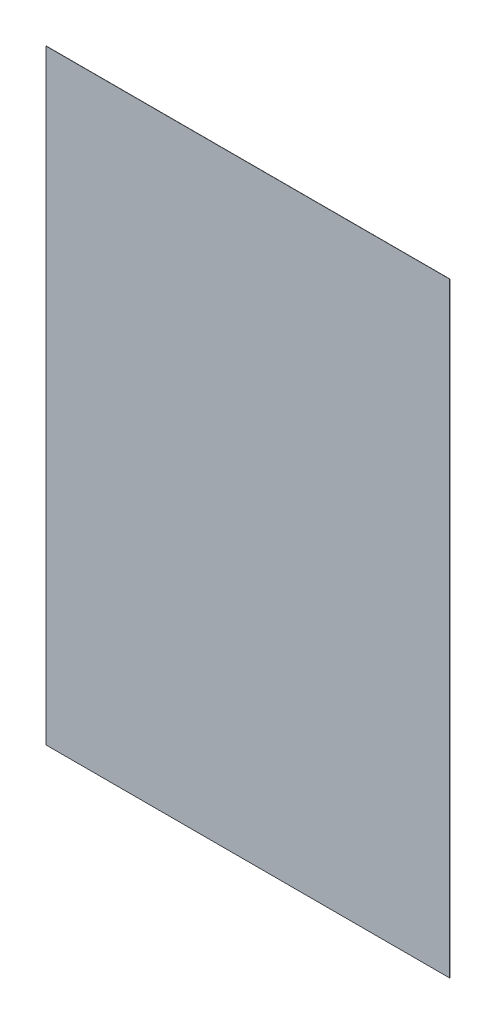
SolidWorks part; units mm, degrees
ref_plane "Front Plane" through (0, 0, 0) normal (0, 0, 1) x (1, 0, 0)
ref_plane "Top Plane" through (0, 0, 0) normal (0, 1, 0) x (1, 0, 0)
ref_plane "Right Plane" through (0, 0, 0) normal (1, 0, 0) x (0, 0, -1)
ref_plane "plane:base-xy" through (0, 0, 0) normal (0, 0, 1) x (1, 0, 0)
sketch "sketch:main-profile" plane through (0, 0, 0) normal (0, 0, 1) x (1, 0, 0)
  line L0 (0, 0) -> (20, 0)
  line L1 (20, 0) -> (20, 30)
  line L2 (20, 30) -> (0, 30)
  line L3 (0, 30) -> (0, 0)
extrude "feature:thin-wall" add sketch "sketch:main-profile" along normal blind 0.01 separate body
